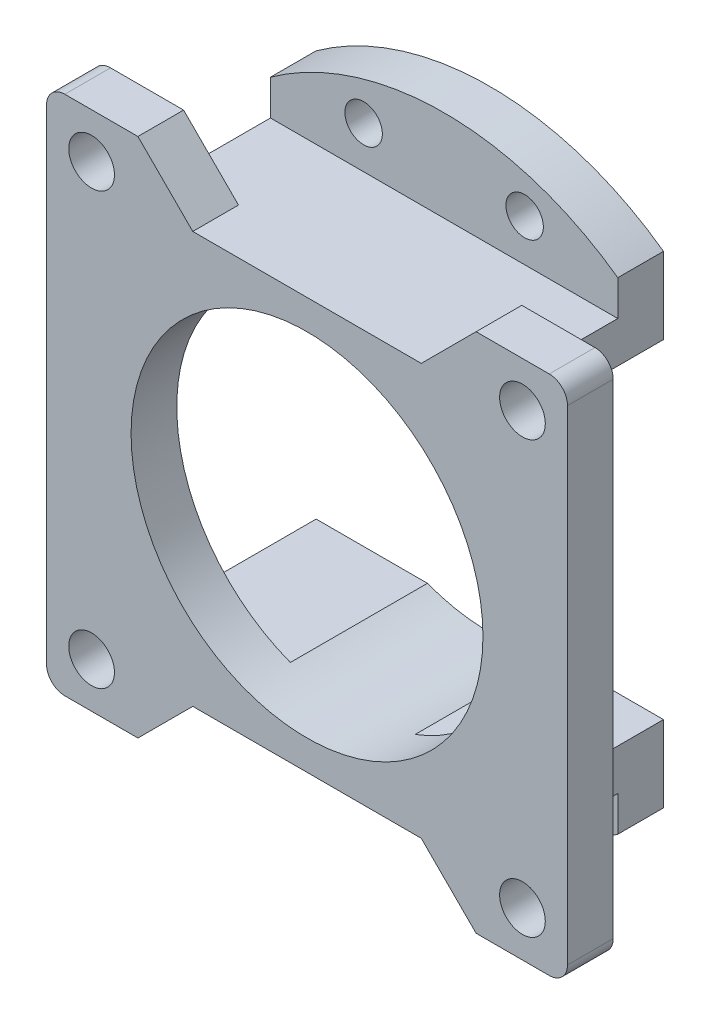
SolidWorks part; units mm, degrees
ref_plane "Front Plane" through (0, 0, 0) normal (0, 0, 1) x (1, 0, 0)
ref_plane "Top Plane" through (0, 0, 0) normal (0, 1, 0) x (1, 0, 0)
ref_plane "Right Plane" through (0, 0, 0) normal (1, 0, 0) x (0, 0, -1)
sketch "Sketch1" plane through (0, 0, 0) normal (0, 0, 1) x (1, 0, 0)
  line L1 (-15.5, -15.5) -> (15.5, -15.5) construction
  line L2 (-15.5, -15.5) -> (-15.5, 15.5) construction
  line L3 (-15.5, 15.5) -> (15.5, 15.5) construction
  line L4 (15.5, -15.5) -> (15.5, 15.5) construction
  line L5 (-15.5, -15.5) -> (15.5, 15.5) construction
  line L6 (-15.5, 15.5) -> (15.5, -15.5) construction
  line L7 (-19, -18) -> (19, -18)
  line L8 (-19, -18) -> (-19, 18)
  line L9 (-19, 18) -> (19, 18)
  line L10 (19, -18) -> (19, 18)
  line L11 (-19, -18) -> (19, 18) construction
  line L12 (-19, 18) -> (19, -18) construction
  circle A0 centre (15.5, 15.5) radius 1.55
  circle A1 centre (-15.5, 15.5) radius 1.55
  circle A2 centre (15.5, -15.5) radius 1.55
  circle A3 centre (-15.5, -15.5) radius 1.55
  circle A4 centre (-15.5, 15.5) radius 2.8 construction
  circle A7 centre (0, 0) radius 11.5
  point P0 (0, 0)
  point P10 (0, 0)
  dimension "D2" = 3.1
  dimension "D3" = 3.1
  dimension "D4" = 3.1
  dimension "D5" = 3.1
  dimension "D7" = 5.6
  dimension "D8" = 36
  dimension "D9" = 23
  dimension "D1" = 31
  dimension "D6" = 38
extrude "Boss-Extrude1" add sketch "Sketch1" along normal blind 5 contours L7 L10 L9 L8 A4 A3 A2 A0
sketch "Sketch2" plane through (0, 0, 5) normal (0, 0, 1) x (1, 0, 0)
  line L8 (19, -18) -> (19, 18) construction
  line L9 (-19, 18) -> (19, 18)
  line L10 (-19, 18) -> (-19, 22.5)
  line L11 (-19, 22.5) -> (19, 22.5)
  line L12 (19, 18) -> (19, 22.5)
  line L13 (-19, 18) -> (19, 22.5) construction
  line L14 (-19, 22.5) -> (19, 18) construction
  line L15 (-19, 18) -> (19, 18) construction
  line L17 (-19, -18) -> (19, -18)
  line L18 (-19, -18) -> (-19, -22.5)
  line L19 (-19, -22.5) -> (19, -22.5)
  line L20 (19, -18) -> (19, -22.5)
  line L21 (-19, -18) -> (19, -22.5) construction
  line L22 (-19, -22.5) -> (19, -18) construction
  point P5 (0, 20.25)
  point P16 (0, -20.25)
  dimension "D1" = 4.5
  dimension "D2" = 4.5
extrude "Boss-Extrude2" add sketch "Sketch2" against normal blind 20
sketch "Sketch3" plane through (0, 0, -15) normal (0, 0, -1) x (-1, 0, 0)
  line L0 (0, 0) -> (0, 28.5) construction
  line L1 (-19, 22.5) -> (19, 22.5)
  line L2 (-19, 22.5) -> (-19, 32.5)
  line L3 (-19, 32.5) -> (19, 32.5)
  line L4 (19, 22.5) -> (19, 32.5)
  line L5 (-19, 22.5) -> (19, 32.5) construction
  line L6 (-19, 32.5) -> (19, 22.5) construction
  line L11 (0, 0) -> (8.807, 27.1051) construction
  line L12 (0, 0) -> (19, 0) construction
  line L13 (19, -18) -> (19, 18) construction
  line L15 (-19, -22.5) -> (19, -22.5)
  line L16 (-19, -22.5) -> (-19, -32.5)
  line L17 (-19, -32.5) -> (19, -32.5)
  line L18 (19, -22.5) -> (19, -32.5)
  line L19 (-19, -22.5) -> (19, -32.5) construction
  line L20 (-19, -32.5) -> (19, -22.5) construction
  circle A2 centre (0, 0) radius 28.5 construction
  circle A3 centre (8.807, 27.1051) radius 2.05
  circle A4 centre (-8.807, 27.1051) radius 2.05
  circle A5 centre (8.807, -27.1051) radius 2.05
  circle A6 centre (-8.807, -27.1051) radius 2.05
  circle A7 centre (0, 0) radius 32.5
  point P5 (0, 27.5)
  point P27 (0, -27.5)
  line M15 (-19, -22.5) -> (19, -22.5)
  dimension "D1" = 10
  dimension "D2" = 38
  dimension "D4" = 18
  dimension "D3" = 57
  dimension "D5" = 4.1
  dimension "D6" = 10
  dimension "D7" = 38
extrude "Boss-Extrude3" add sketch "Sketch3" against normal blind 5 contours L4 A7 L2 L1 A3 A4 | L16 A7 L18 A6 A5 M15
fillet "Fillet1" [suppressed] radius 2
sketch "Sketch4" plane through (0, 0, 5) normal (0, 0, 1) x (1, 0, 0)
  line L8 (-28.5, -28.5) -> (28.5, -28.5)
  line L9 (-28.5, -28.5) -> (-28.5, 28.5)
  line L10 (-28.5, 28.5) -> (28.5, 28.5)
  line L11 (28.5, -28.5) -> (28.5, 28.5)
  line L12 (-28.5, -28.5) -> (28.5, 28.5) construction
  line L13 (-28.5, 28.5) -> (28.5, -28.5) construction
  line L14 (-23.57, -23.57) -> (23.57, -23.57) construction
  line L15 (-23.57, -23.57) -> (-23.57, 23.57) construction
  line L16 (-23.57, 23.57) -> (23.57, 23.57) construction
  line L17 (23.57, -23.57) -> (23.57, 23.57) construction
  line L18 (-23.57, -23.57) -> (23.57, 23.57) construction
  line L19 (-23.57, 23.57) -> (23.57, -23.57) construction
  circle A8 centre (-23.57, 23.57) radius 2.5
  circle A9 centre (23.57, 23.57) radius 2.5
  circle A10 centre (23.57, -23.57) radius 2.5
  circle A11 centre (-23.57, -23.57) radius 2.5
  point P0 (0, 0)
  point P5 (0, 0)
  dimension "D3" = 5
  dimension "D4" = 5
  dimension "D5" = 5
  dimension "D6" = 5
  dimension "D1" = 57
  dimension "D2" = 47.14
extrude "Boss-Extrude4" add sketch "Sketch4" against normal blind 5
fillet "Fillet2" radius 2 4 edges at (28.5, -28.5, 2.5) (28.5, 28.5, 2.5) (-28.5, 28.5, 2.5) (-28.5, -28.5, 2.5)
sketch "Sketch6" plane through (0, 0, 5) normal (0, 0, 1) x (1, 0, 0)
  circle A0 centre (0, 0) radius 19.25
  dimension "D1" = 38.5
extrude "Cut-Extrude2" cut sketch "Sketch6" against normal through all
sketch "Sketch7" plane through (0, 0, 5) normal (0, 0, 1) x (1, 0, 0)
  line L0 (-18.5, 28.5) -> (-12.5, 22.5)
  line L1 (-26.5, 28.5) -> (26.5, 28.5) construction
  line L2 (-12.5, 22.5) -> (12.5, 22.5)
  line L3 (12.5, 22.5) -> (18.5, 28.5)
  line L4 (-28.5, -26.5) -> (-28.5, 26.5) construction
  line L5 (28.5, -26.5) -> (28.5, 26.5) construction
  line L6 (-18.5, 28.5) -> (18.5, 28.5)
  line L7 (0, 0) -> (19.25, 0) construction
  line L8 (-18.5, -28.5) -> (18.5, -28.5)
  line L9 (12.5, -22.5) -> (18.5, -28.5)
  line L10 (-12.5, -22.5) -> (12.5, -22.5)
  line L11 (-18.5, -28.5) -> (-12.5, -22.5)
  circle A12 centre (0, 0) radius 19.25 construction
  line M10 (-26.5, -28.5) -> (26.5, -28.5)
  line M14 (26.5, 28.5) -> (-26.5, 28.5)
  dimension "D1" = 135
  dimension "D2" = 6
  dimension "D3" = 10
  dimension "D4" = 10
extrude "Cut-Extrude3" cut sketch "Sketch7" against normal blind 5 contours L2 L3 L0 M14 | L11 L9 L10 M10
